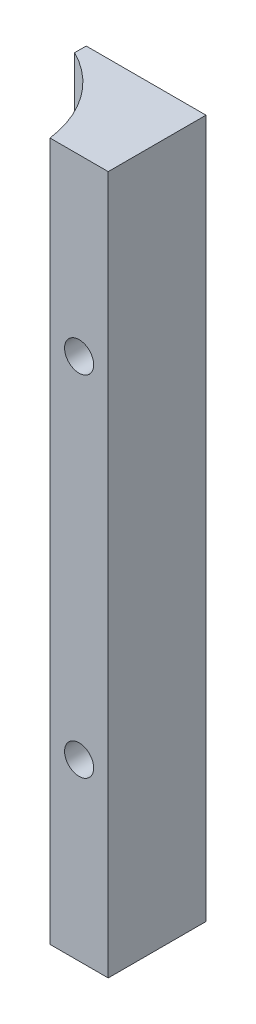
SolidWorks part; units mm, degrees
ref_plane "Front" through (0, 0, 0) normal (0, 0, 1) x (1, 0, 0)
ref_plane "Top" through (0, 0, 0) normal (0, 1, 0) x (1, 0, 0)
ref_plane "Right" through (0, 0, 0) normal (1, 0, 0) x (0, 0, -1)
sketch "Sketch1" plane through (0, 0, 0) normal (0, 1, 0) x (1, 0, 0)
  line L0 (0, 0) -> (0, 8.4)
  line L1 (0, 8.4) -> (-10.2908, 8.4)
  line L2 (-10.2908, 8.4) -> (-10.2908, 7.4)
  line L3 (-5, 0) -> (0, 0)
  arc A0 (-10.2908, 7.4) -> (-5, 0) centre (-14.5687, -1.25) cw
  dimension "D3" = 9.65
  dimension "D1" = 5
  dimension "D2" = 8.4
  dimension "D4" = 1.25
  dimension "D5" = 1
extrude "Boss-Extrude1" add sketch "Sketch1" along normal blind 60
sketch "Sketch2" plane through (0, 0, 0) normal (0, 0, 1) x (1, 0, 0)
  line L0 (-2.5, 60) -> (-2.5, 0) construction
  line L1 (-5, 60) -> (0, 60) construction
  line L2 (-5, 0) -> (0, 0) construction
  point P6 (-2.5, 45)
  point P7 (-2.5, 15)
  dimension "D1" = 15
  dimension "D2" = 15
hole_wizard "Ø2.5mm Dowel Hole1" positions "3DSketch1" profile "Sketch3" hole size "Ø2.5" standard "ANSI Metric" end condition up to next
sketch3d "3DSketch1"
  point P0 (-2.5, 45, 0)
  point P3 (-2.5, 15, 0)
sketch "Sketch3" plane through (-2.5, 45, 0) normal (1, 0, 0) x (0, -1, 0)
  line L0 (0, 0) -> (0, 8.4)
  line L1 (0, 8.4) -> (1.25, 8.4)
  line L2 (1.25, 8.4) -> (1.25, 0)
  line L5 (1.25, 0) -> (0, 0)
  line L11 (0, -6.35) -> (0, 107.95) construction
  dimension "Thru Hole Dia." = 2.5
  dimension "Thru Hole Depth" = 8.4
